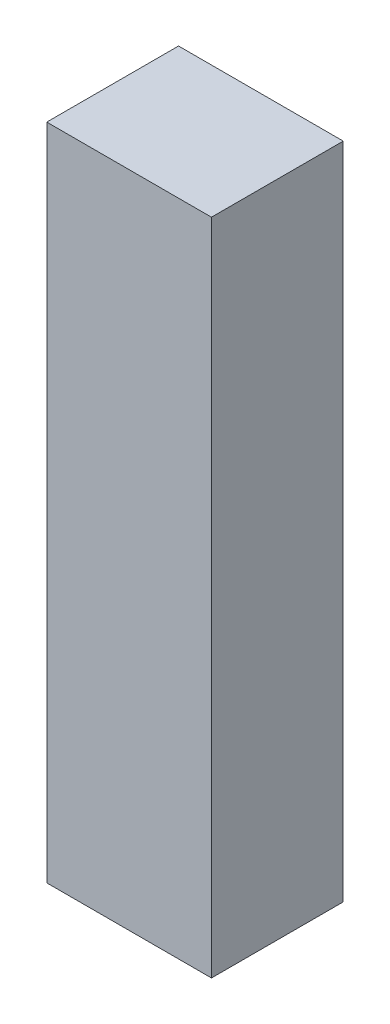
SolidWorks part; units mm, degrees
ref_plane "Front Plane" through (0, 0, 0) normal (0, 0, 1) x (1, 0, 0)
ref_plane "Top Plane" through (0, 0, 0) normal (0, 1, 0) x (1, 0, 0)
ref_plane "Right Plane" through (0, 0, 0) normal (1, 0, 0) x (0, 0, -1)
other "Configuration Table"
sketch "Sketch1" plane through (0, 0, 0) normal (0, 0, 1) x (1, 0, 0)
  line L1 (440, 330) -> (490, 330)
  line L2 (440, 330) -> (440, 530)
  line L3 (440, 530) -> (490, 530)
  line L4 (490, 330) -> (490, 530)
extrude "TOPPING_arka_duvar_pano_surucu_5_1" add sketch "Sketch1" against normal blind 40 from offset 736 separate body
